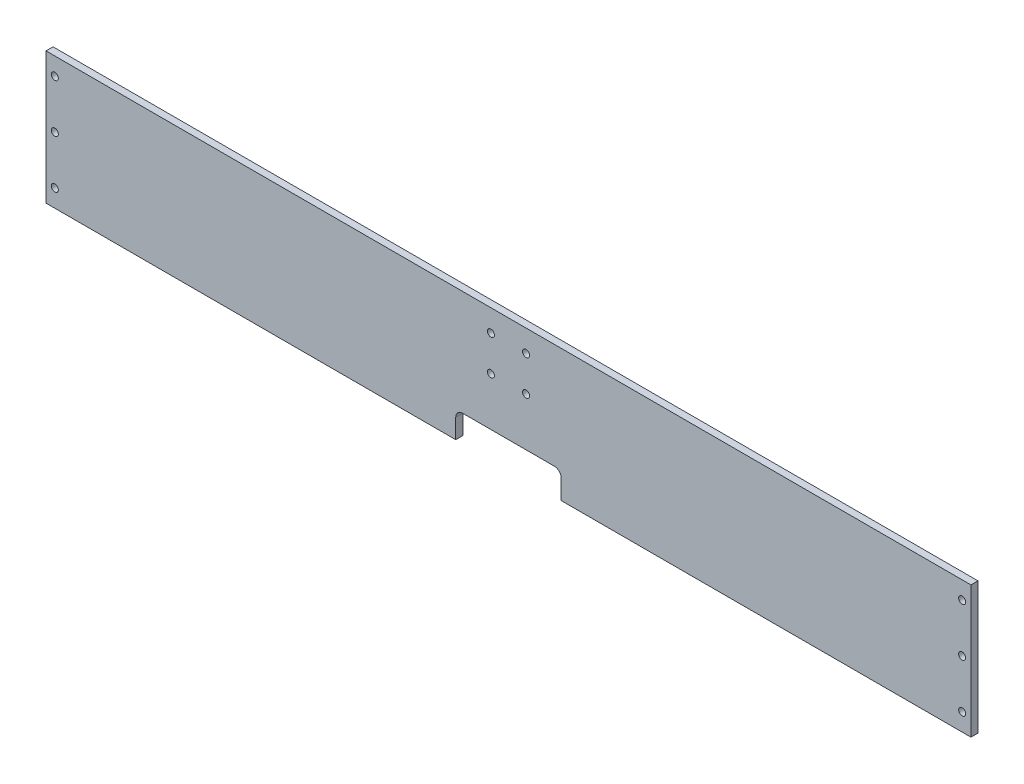
SolidWorks part; units mm, degrees
ref_plane "Piano frontale" through (0, 0, 0) normal (0, 0, 1) x (1, 0, 0)
ref_plane "Piano superiore" through (0, 0, 0) normal (0, 1, 0) x (1, 0, 0)
ref_plane "Piano destro" through (0, 0, 0) normal (1, 0, 0) x (0, 0, -1)
sketch "Schizzo1" plane through (0, 0, 0) normal (0, 0, 1) x (1, 0, 0)
  line L0 (5, 75) -> (5, 0) construction
  line L1 (0, 0) -> (526, 0)
  line L2 (0, 0) -> (0, 75)
  line L3 (0, 75) -> (526, 75)
  line L4 (526, 0) -> (526, 75)
  line L5 (0, 37.5) -> (10.4526, 37.5) construction
  line L6 (263, 75) -> (263, 0) construction
  circle A0 centre (5, 37.5) radius 2
  circle A1 centre (5, 65) radius 2
  circle A2 centre (5, 10) radius 2
  circle A3 centre (521, 10) radius 2
  circle A4 centre (521, 65) radius 2
  circle A5 centre (521, 37.5) radius 2
  dimension "D4" = 4
  dimension "D5" = 5
  dimension "D1" = 75
  dimension "D2" = 526
  dimension "D3" = 27.5
extrude "Estrusione-Estrusione1" add sketch "Schizzo1" against normal blind 4
sketch "Schizzo2" plane through (0, 0, 0) normal (0, 0, 1) x (1, 0, 0)
  line L0 (263, 75) -> (263, 0) construction
  line L1 (526, 75) -> (0, 75) construction
  line L2 (0, 37.5) -> (526, 37.5) construction
  line L3 (0, 0) -> (526, 0) construction
  line L9 (0, 75) -> (0, 0) construction
  line L10 (526, 0) -> (526, 75) construction
  line L11 (233, 15) -> (293, -15) construction
  line L12 (233, -15) -> (293, 15) construction
  line L13 (293, -15) -> (293, 11)
  line L14 (237, 15) -> (289, 15)
  line L15 (233, -15) -> (233, 11)
  line L16 (233, -15) -> (293, -15)
  circle A0 centre (253, 62.5) radius 2
  circle A1 centre (273, 62.5) radius 2
  arc A2 (237, 15) -> (233, 11) centre (237, 11) ccw
  arc A3 (293, 11) -> (289, 15) centre (289, 11) ccw
  circle A4 centre (253, 42.5) radius 2
  circle A5 centre (273, 42.5) radius 2
  dimension "D3" = 4
  dimension "D1" = 25
  dimension "D2" = 10
  dimension "D4" = 20
  dimension "D5" = 20
extrude "Taglio-Estrusione1" cut sketch "Schizzo2" against normal blind 4
